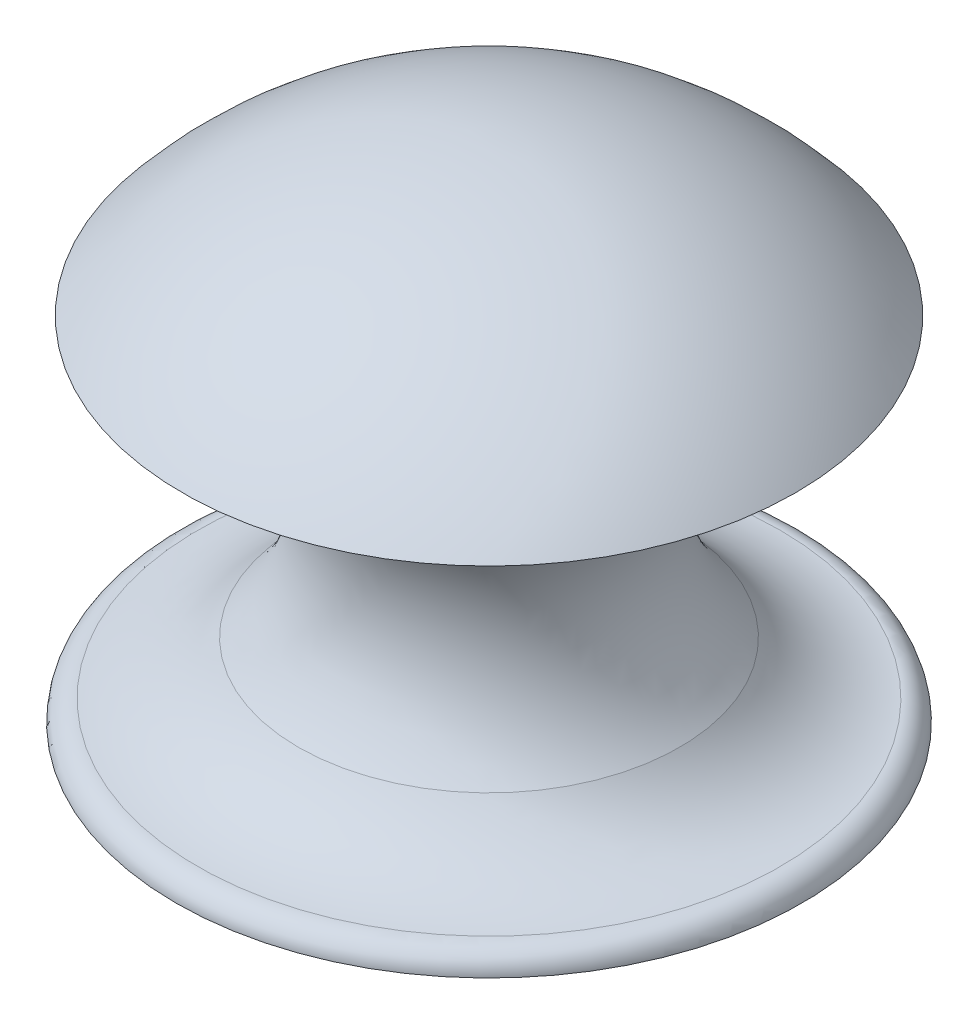
SolidWorks part; units mm, degrees
ref_plane "Front Plane" through (0, 0, 0) normal (0, 0, 1) x (1, 0, 0)
ref_plane "Top Plane" through (0, 0, 0) normal (0, 1, 0) x (1, 0, 0)
ref_plane "Right Plane" through (0, 0, 0) normal (1, 0, 0) x (0, 0, -1)
sketch "Sketch1" plane through (0, 0, 0) normal (0, 0, 1) x (1, 0, 0)
  line L0 (0, 0) -> (0, 27)
  line L1 (0, 0) -> (17, 0)
  arc A0 (16.666, 19.1503) -> (0, 27) centre (0, 5.383) ccw
  arc A2 (10.3557, 4.0144) -> (16.666, 19.1503) centre (16.6664, 10.2668) cw
  arc A3 (17, 0) -> (15.829, 1.14) centre (15.8445, -0.0155) ccw
  arc A4 (10.3557, 4.0144) -> (15.829, 1.14) centre (16.3463, 8.773) ccw
  dimension "D1" = 17
  dimension "D2" = 27
revolve "Revolve1" add sketch "Sketch1" angle 360 about L0
sketch "Sketch3" plane through (0, 0, 0) normal (0, -1, 0) x (1, 0, 0)
  circle A0 centre (0, 0) radius 1.5
  dimension "D1" = 3
extrude "Cut-Extrude2" cut sketch "Sketch3" against normal blind 13
